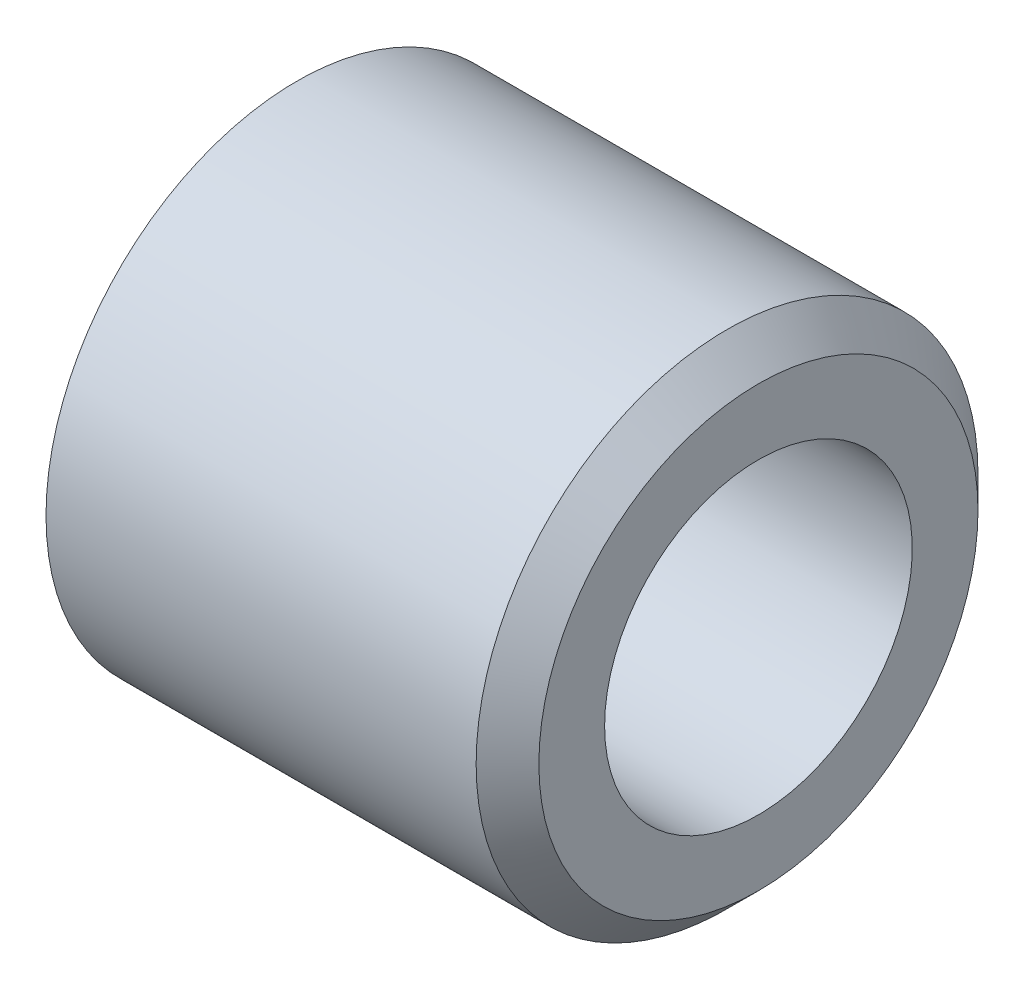
SolidWorks part; units mm, degrees
material "Tin Bearing Bronze"
ref_plane "Plane1" through (0, 0, 0) normal (0, 0, 1) x (1, 0, 0)
ref_plane "Plane2" through (0, 0, 0) normal (0, 1, 0) x (1, 0, 0)
ref_plane "Plane3" through (0, 0, 0) normal (1, 0, 0) x (0, 0, -1)
sketch "Sketch1" plane through (0, 0, 0) normal (0, 0, 1) x (1, 0, 0)
  line L0 (0, 0) -> (76.2, 0) construction
  line L1 (0, 3.9624) -> (0, 5.1791)
  line L4 (0, 5.1791) -> (8.8776, 5.1791)
  line L5 (8.8776, 5.1791) -> (9.525, 4.5317)
  line L6 (9.525, 4.5317) -> (9.525, 3.175)
  line L7 (9.525, 3.175) -> (0.7874, 3.175)
  line L8 (8.8776, -5.1791) -> (9.525, -4.5317) construction
  line L9 (9.525, -3.175) -> (0, -3.175) construction
  line L10 (0, -5.1791) -> (8.8776, -5.1791) construction
  arc A1 (0, 3.9624) -> (0.7874, 3.175) centre (0.7874, 3.9624) ccw
  point P20 (0, 3.175)
  dimension "Head_radius" = 0.7874
  dimension "Hole_dia" = 6.35
  dimension "Body_dia" = 10.3581
  dimension "Body_len" = 9.525
  dimension "D1" = 9.0634
  dimension "D2" = 45
revolve "BaseBody" add sketch "Sketch1" angle 360 about L0
equation "\"D1@Sketch1\" = \"Body_dia@Sketch1\" * .875"
